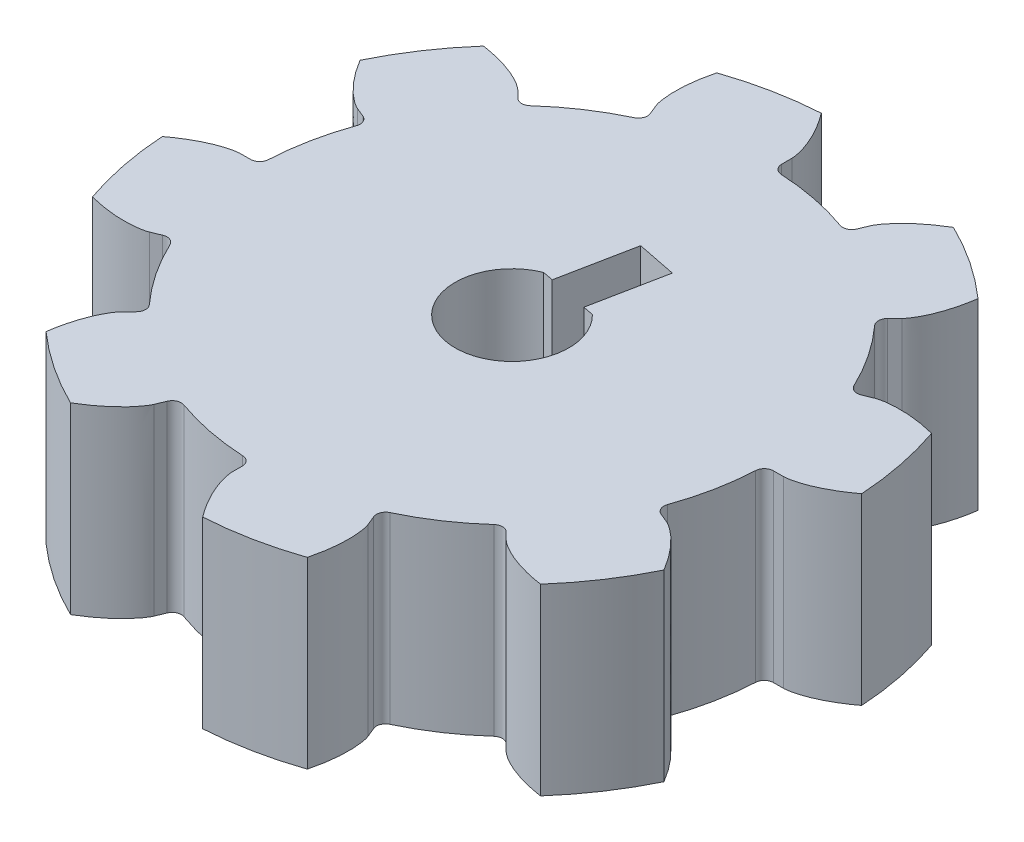
SolidWorks part; units mm, degrees
ref_plane "正面" through (0, 0, 0) normal (0, 0, 1) x (1, 0, 0)
ref_plane "平面" through (0, 0, 0) normal (0, 1, 0) x (1, 0, 0)
ref_plane "右側面" through (0, 0, 0) normal (1, 0, 0) x (0, 0, -1)
sketch "ｽｹｯﾁ1" plane through (0, 0, 0) normal (0, 1, 0) x (1, 0, 0)
  line L0 (0, 0) -> (0, 102.2347) construction
  line L1 (-97.1662, 16) -> (83.1097, 16) construction
  line L2 (-58.4661, -5.2799) -> (63.2436, 39.0188) construction
  circle A0 centre (0, 0) radius 16 construction
  circle A1 centre (0, 0) radius 15.0351 construction
  point P9 (0, 16)
  dimension "D2" = 32
  dimension "D1" = 20
sketch "ｽｹｯﾁ2" plane through (0, 0, 0) normal (0, 1, 0) x (1, 0, 0)
  line L0 (-5.1423, 14.1284) -> (0, 16) construction
  line L1 (-187996.9903, -68409.3086) -> (188001.7678, 68443.0475) construction
  line L2 (-4.3836, 14.3818) -> (0.0857, 15.7441) construction
  line L3 (-3.6125, 14.5946) -> (0.1463, 15.525) construction
  line L4 (-2.8312, 14.7661) -> (0.1861, 15.3446) construction
  line L5 (-2.0419, 14.8958) -> (0.2094, 15.2044) construction
  line L6 (-1.2468, 14.9833) -> (0.2205, 15.1054) construction
  line L7 (-0.4482, 15.0284) -> (0.2239, 15.0484) construction
  line L8 (-5.8864, 13.8349) -> (-0.1148, 16.2906) construction
  line L9 (-6.6139, 13.5022) -> (-0.2626, 16.6133) construction
  line L10 (-7.3226, 13.1314) -> (-0.4471, 16.9655) construction
  line L11 (-8.0106, 12.7233) -> (-0.6717, 17.3439) construction
  line L12 (-8.676, 12.2793) -> (-0.9398, 17.7453) construction
  line L13 (-9.3168, 11.8005) -> (-1.2544, 18.1659) construction
  line L14 (0, 0) -> (-6.4709, 32.5312) construction
  line L15 (0, -200000) -> (0, 200102.2347) construction
  circle A0 centre (0, 0) radius 15.0351 construction
  arc A1 (-5.1423, 14.1284) -> (-4.3836, 14.3818) centre (0, 0) cw
  arc A2 (-4.3836, 14.3818) -> (-3.6125, 14.5946) centre (0, 0) cw
  arc A3 (-3.6125, 14.5946) -> (-2.8312, 14.7661) centre (0, 0) cw
  arc A4 (-2.8312, 14.7661) -> (-2.0419, 14.8958) centre (0, 0) cw
  arc A5 (-2.0419, 14.8958) -> (-1.2468, 14.9833) centre (0, 0) cw
  arc A6 (-1.2468, 14.9833) -> (-0.4482, 15.0284) centre (0, 0) cw
  arc A7 (-5.1423, 14.1284) -> (-5.8864, 13.8349) centre (0, 0) ccw
  arc A8 (-5.8864, 13.8349) -> (-6.6139, 13.5022) centre (0, 0) ccw
  arc A9 (-6.6139, 13.5022) -> (-7.3226, 13.1314) centre (0, 0) ccw
  arc A10 (-7.3226, 13.1314) -> (-8.0106, 12.7233) centre (0, 0) ccw
  arc A11 (-8.0106, 12.7233) -> (-8.676, 12.2793) centre (0, 0) ccw
  arc A12 (-8.676, 12.2793) -> (-9.3168, 11.8005) centre (0, 0) ccw
  arc A13 (-5.1423, 14.1284) -> (0.2241, 15.0334) centre (0, 0) cw
  spline S0 degree 3 poles (-1.2544, 18.1659) (-1.0462, 17.9022) (-0.7654, 17.5086) (-0.4508, 16.9797) (-0.2659, 16.6275) (-0.1177, 16.3048) (-0.0025, 16.0142) (0.0836, 15.7583) (0.1447, 15.5393) (0.1848, 15.3589) (0.2085, 15.2186) (0.2204, 15.1146) (0.224, 15.0574) (0.2241, 15.0334) knots 0 0 0 0 0.287256 0.412688 0.52599 0.627162 0.716204 0.793115 0.857896 0.910546 0.951067 0.979456 1 1 1 1
  spline S1 degree 3 poles (-5.7929, 17.2632) (-5.8843, 16.9399) (-5.9931, 16.4688) (-6.0814, 15.8597) (-6.1175, 15.4636) (-6.1309, 15.1087) (-6.1261, 14.7961) (-6.1077, 14.5268) (-6.0803, 14.301) (-6.0483, 14.119) (-6.0165, 13.9804) (-5.9877, 13.8797) (-5.9692, 13.8255) (-5.9601, 13.8033) knots 0 0 0 0 0.287256 0.412688 0.52599 0.627162 0.716204 0.793115 0.857896 0.910546 0.951067 0.979456 1 1 1 1
  dimension "D1" = 5.4723
  dimension "D3" = 4.6723
  dimension "D4" = 3.8723
  dimension "D5" = 3.0723
  dimension "D6" = 2.2723
  dimension "D7" = 1.4723
  dimension "D8" = 0.6723
  dimension "D9" = 6.2723
  dimension "D10" = 7.0723
  dimension "D11" = 7.8723
  dimension "D12" = 8.6723
  dimension "D13" = 9.4723
  dimension "D14" = 10.2723
  dimension "D15" = 11.25
  dimension "D2" = 0.8
sketch "ｽｹｯﾁ3" plane through (0, 0, 0) normal (0, 1, 0) x (1, 0, 0)
  line L0 (0.2241, 15.0334) -> (0.2241, 13.9982)
  line L1 (0, 0) -> (-6.4709, 32.5312) construction
  line L2 (0, 0) -> (-6.4709, 32.5312) construction
  line L3 (-5.9601, 13.8033) -> (-5.5639, 12.8469)
  arc A0 (0.2241, 13.9982) -> (-5.5639, 12.8469) centre (0, 0) ccw
  arc A1 (-1.1008, 17.9663) -> (-5.8584, 17.02) centre (0, 0) ccw
  spline S0 degree 3 poles (-1.2544, 18.1659) (-1.0462, 17.9022) (-0.7654, 17.5086) (-0.4508, 16.9797) (-0.2659, 16.6275) (-0.1177, 16.3048) (-0.0025, 16.0142) (0.0836, 15.7583) (0.1447, 15.5393) (0.1848, 15.3589) (0.2085, 15.2186) (0.2204, 15.1146) (0.224, 15.0574) (0.2241, 15.0334) knots 0 0 0 0 0.287256 0.412688 0.52599 0.627162 0.716204 0.793115 0.857896 0.910546 0.951067 0.979456 1 1 1 1 construction
  spline S1 degree 3 poles (-5.7929, 17.2632) (-5.8843, 16.9399) (-5.9931, 16.4688) (-6.0814, 15.8597) (-6.1175, 15.4636) (-6.1309, 15.1087) (-6.1261, 14.7961) (-6.1077, 14.5268) (-6.0803, 14.301) (-6.0483, 14.119) (-6.0165, 13.9804) (-5.9877, 13.8797) (-5.9692, 13.8255) (-5.9601, 13.8033) knots 0 0 0 0 0.287256 0.412688 0.52599 0.627162 0.716204 0.793115 0.857896 0.910546 0.951067 0.979456 1 1 1 1 construction
  spline S2 degree 3 poles (-1.1008, 17.9663) (-0.9496, 17.7647) (-0.7225, 17.4365) (-0.4508, 16.9797) (-0.2659, 16.6275) (-0.1177, 16.3048) (-0.0025, 16.0142) (0.0836, 15.7583) (0.1447, 15.5393) (0.1848, 15.3589) (0.2085, 15.2186) (0.2204, 15.1146) (0.224, 15.0574) (0.2241, 15.0334) knots 0 0 0 0 0.232146 0.367277 0.48934 0.598334 0.694261 0.777119 0.846908 0.90363 0.947283 0.977868 1 1 1 1
  spline S3 degree 3 poles (-5.8584, 17.02) (-5.9209, 16.7758) (-6.0052, 16.3857) (-6.0814, 15.8597) (-6.1175, 15.4636) (-6.1309, 15.1087) (-6.1261, 14.7961) (-6.1077, 14.5268) (-6.0803, 14.301) (-6.0483, 14.119) (-6.0165, 13.9804) (-5.9877, 13.8797) (-5.9692, 13.8255) (-5.9601, 13.8033) knots 0 0 0 0 0.232146 0.367277 0.48934 0.598334 0.694261 0.777119 0.846908 0.90363 0.947283 0.977868 1 1 1 1
  point P4 (-5.8584, 17.02)
  point P6 (-1.1008, 17.9663)
  dimension "D1" = 28
  dimension "D2" = 4
sketch "ｽｹｯﾁ4" plane through (0, 0, 0) normal (0, 1, 0) x (1, 0, 0)
  circle A0 centre (0, 0) radius 14
  dimension "D1" = 28
extrude "ﾎﾞｽ - 押し出し1" add sketch "ｽｹｯﾁ4" along normal blind 10
extrude "ﾎﾞｽ - 押し出し2" add sketch "ｽｹｯﾁ3" along normal blind 10
fillet "ﾌｨﾚｯﾄ1" radius 0.5 2 edges at (-5.5639, 5, -12.8469) (0.2241, 5, -13.9982)
pattern_circular "円形ﾊﾟﾀｰﾝ1" count 8 over 360 about axis through (0, 10, 0) along (0, 1, 0) of "ﾎﾞｽ - 押し出し2", "ﾌｨﾚｯﾄ1"
sketch "ｽｹｯﾁ5" plane through (0, 10, 0) normal (0, 1, 0) x (1, 0, 0)
  line L0 (2.6929, 13.5382) -> (-9751.8232, -49025.7258) construction
  line L7 (-1.1485, 2.8794) -> (-0.5716, 2.7646)
  line L8 (-0.5716, 2.7646) -> (0.2282, 6.7859)
  line L13 (0.2282, 6.7859) -> (2.386, 6.3567)
  line L14 (2.386, 6.3567) -> (1.5861, 2.3354)
  line L15 (1.5861, 2.3354) -> (2.163, 2.2207)
  arc A0 (-1.1485, 2.8794) -> (2.163, 2.2207) centre (0, 0) ccw
  arc A1 (4.705, 13.1857) -> (0.6991, 13.9825) centre (0, 0) ccw construction
  arc A2 (-4.705, -13.1857) -> (-0.6991, -13.9825) centre (0, 0) ccw construction
  point P5 (1.3071, 6.5713)
  point P13 (2.7313, 13.731)
  point P19 (-2.7313, -13.731)
  dimension "D1" = 6.2
  dimension "D2" = 2.6
  dimension "D3" = 2.2
  dimension "D4" = 4.1
extrude "ｶｯﾄ - 押し出し1" cut sketch "ｽｹｯﾁ5" against normal through all
equation "\"D3@ｽｹｯﾁ2\"=\"D1@ｽｹｯﾁ2\"-\"D2@ｽｹｯﾁ2\""
equation "\"D4@ｽｹｯﾁ2\"=\"D3@ｽｹｯﾁ2\"-\"D2@ｽｹｯﾁ2\""
equation "\"D5@ｽｹｯﾁ2\"=\"D4@ｽｹｯﾁ2\"-\"D2@ｽｹｯﾁ2\""
equation "\"D6@ｽｹｯﾁ2\"=\"D5@ｽｹｯﾁ2\"-\"D2@ｽｹｯﾁ2\""
equation "\"D7@ｽｹｯﾁ2\"=\"D6@ｽｹｯﾁ2\"-\"D2@ｽｹｯﾁ2\""
equation "\"D8@ｽｹｯﾁ2\"=\"D7@ｽｹｯﾁ2\"-\"D2@ｽｹｯﾁ2\""
equation "\"D9@ｽｹｯﾁ2\"=\"D1@ｽｹｯﾁ2\"+\"D2@ｽｹｯﾁ2\""
equation "\"D10@ｽｹｯﾁ2\"=\"D9@ｽｹｯﾁ2\"+\"D2@ｽｹｯﾁ2\""
equation "\"D11@ｽｹｯﾁ2\"=\"D10@ｽｹｯﾁ2\"+\"D2@ｽｹｯﾁ2\""
equation "\"D12@ｽｹｯﾁ2\"=\"D11@ｽｹｯﾁ2\"+\"D2@ｽｹｯﾁ2\""
equation "\"D13@ｽｹｯﾁ2\"=\"D12@ｽｹｯﾁ2\"+\"D2@ｽｹｯﾁ2\""
equation "\"D14@ｽｹｯﾁ2\"=\"D13@ｽｹｯﾁ2\"+\"D2@ｽｹｯﾁ2\""
equation "\"D15@ｽｹｯﾁ2\"=90/8"
